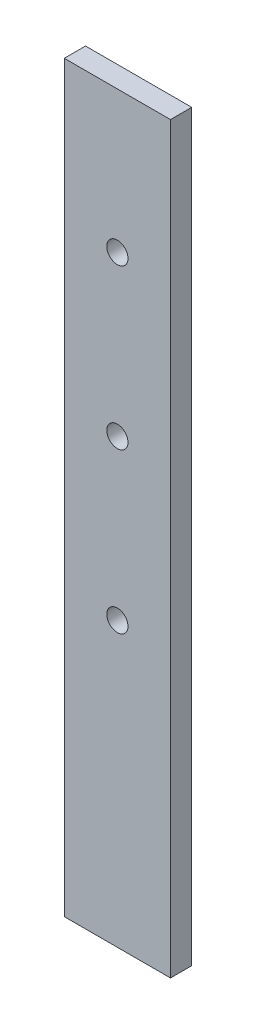
SolidWorks part; units mm, degrees
ref_plane "Front Plane" through (0, 0, 0) normal (0, 0, 1) x (1, 0, 0)
ref_plane "Top Plane" through (0, 0, 0) normal (0, 1, 0) x (1, 0, 0)
ref_plane "Right Plane" through (0, 0, 0) normal (1, 0, 0) x (0, 0, -1)
sketch "Sketch1" plane through (0, 0, 0) normal (0, 0, 1) x (1, 0, 0)
  line L0 (30, 210) -> (30, 0)
  line L1 (0, 0) -> (30, 0)
  line L2 (0, 0) -> (0, 210)
  line L3 (0, 210) -> (30, 210)
  dimension "D1" = 30
extrude "Boss-Extrude1" add sketch "Sketch1" along normal blind 6
sketch "Sketch2" plane through (0, 0, 6) normal (0, 0, 1) x (1, 0, 0)
  line L0 (15, 0) -> (15, 217.1659) construction
  line L1 (0, 0) -> (30, 0) construction
  line L2 (30, 210) -> (0, 210) construction
  circle A0 centre (15, 170) radius 3
  circle A1 centre (15, 125) radius 3
  circle A2 centre (15, 80) radius 3
  dimension "D1" = 6
  dimension "D2" = 6
  dimension "D3" = 6
  dimension "D4" = 40
  dimension "D5" = 85
  dimension "D6" = 130
extrude "Cut-Extrude1" cut sketch "Sketch2" against normal blind 6
